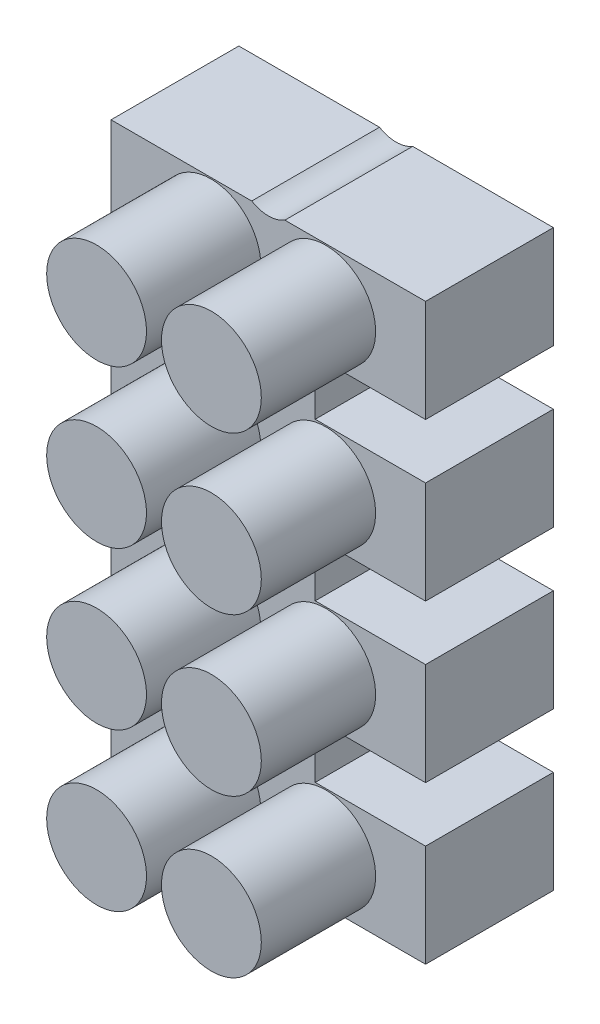
SolidWorks part; units mm, degrees
ref_plane "Front Plane" through (0, 0, 0) normal (0, 0, 1) x (1, 0, 0)
ref_plane "Top Plane" through (0, 0, 0) normal (0, 1, 0) x (1, 0, 0)
ref_plane "Right Plane" through (0, 0, 0) normal (1, 0, 0) x (0, 0, -1)
sketch "Sketch1" plane through (0, 0, 0) normal (0, 0, 1) x (1, 0, 0)
  line L1 (-8.001, -6.604) -> (8.001, -6.604)
  line L2 (-8.001, -6.604) -> (-8.001, 6.604)
  line L3 (-8.001, 6.604) -> (8.001, 6.604)
  line L4 (8.001, -6.604) -> (8.001, 6.604)
  line L5 (-8.001, -6.604) -> (8.001, 6.604) construction
  line L6 (-8.001, 6.604) -> (8.001, -6.604) construction
  point P0 (0, 0)
  dimension "D1" = 13.208
  dimension "D2" = 16.002
extrude "Boss-Extrude1" add sketch "Sketch1" along normal blind 6.5024
sketch "Sketch2" plane through (0, 0, 6.5024) normal (0, 0, 1) x (1, 0, 0)
  line L0 (8.001, -6.604) -> (8.001, 6.604) construction
  line L1 (8.001, 1.397) -> (2.3876, 1.397)
  line L2 (8.001, 1.397) -> (8.001, -1.397)
  line L3 (8.001, -1.397) -> (2.3876, -1.397)
  line L4 (2.3876, 1.397) -> (2.3876, -1.397)
  line L5 (2.3876, 0) -> (0, 0) construction
  dimension "D1" = 2.794
  dimension "D2" = 5.6134
extrude "Cut-Extrude1" cut sketch "Sketch2" against normal through all
hole_wizard "#4 Clearance Hole1" positions "Sketch4" profile "Sketch3" hole size "#4" standard "ANSI Inch" end condition through all
sketch "Sketch4" plane through (0, 0, 6.5024) normal (0, 0, 1) x (1, 0, 0)
  point P0 (0, 0)
sketch "Sketch3" plane through (0, 0, 6.5024) normal (1, 0, 0) x (0, -1, 0)
  line L0 (0, 0) -> (0, 6.5024)
  line L1 (0, 6.5024) -> (1.6319, 6.5024)
  line L2 (1.6319, 6.5024) -> (1.6319, 0)
  line L5 (1.6319, 0) -> (0, 0)
  line L11 (0, -6.35) -> (0, 107.95) construction
  dimension "Thru Hole Dia." = 3.2639
  dimension "Thru Hole Depth" = 6.5024
sketch "Sketch5" plane through (0, 0, 6.5024) normal (0, 0, 1) x (1, 0, 0)
  line L0 (2.921, -4.0005) -> (8.001, -4.0005) construction
  line L2 (8.001, -6.604) -> (8.001, -1.397) construction
  circle A0 centre (2.921, -4.0005) radius 2.54
  dimension "D1" = 5.08
  dimension "D2" = 5.08
extrude "Boss-Extrude2" add sketch "Sketch5" along normal blind 5.8166
sketch "Sketch6" plane through (0, 0, 6.5024) normal (0, 0, 1) x (1, 0, 0)
  line L1 (8.001, 1.397) -> (-8.001, 1.397)
  line L2 (8.001, 1.397) -> (8.001, 6.604)
  line L3 (8.001, 6.604) -> (-8.001, 6.604)
  line L4 (-8.001, 1.397) -> (-8.001, 6.604)
extrude "Cut-Extrude2" cut sketch "Sketch6" against normal through all
mirror "Mirror4" about plane through (0, 0, 0) normal (1, 0, 0) of "Cut-Extrude1", "Boss-Extrude2"
pattern_linear "LPattern1" count 4 spacing 8.001 along (0, 1, 0) of "Boss-Extrude1", "Cut-Extrude1", "#4 Clearance Hole1", "Boss-Extrude2", "Mirror4"
sketch "Sketch7" plane through (0, 0, 6.5024) normal (0, 0, 1) x (1, 0, 0)
  line L1 (-8.001, 30.607) -> (8.001, 30.607)
  line L2 (-8.001, 30.607) -> (-8.001, 22.606)
  line L3 (-8.001, 22.606) -> (8.001, 22.606)
  line L4 (8.001, 30.607) -> (8.001, 22.606)
extrude "Cut-Extrude3" cut sketch "Sketch7" against normal through all
